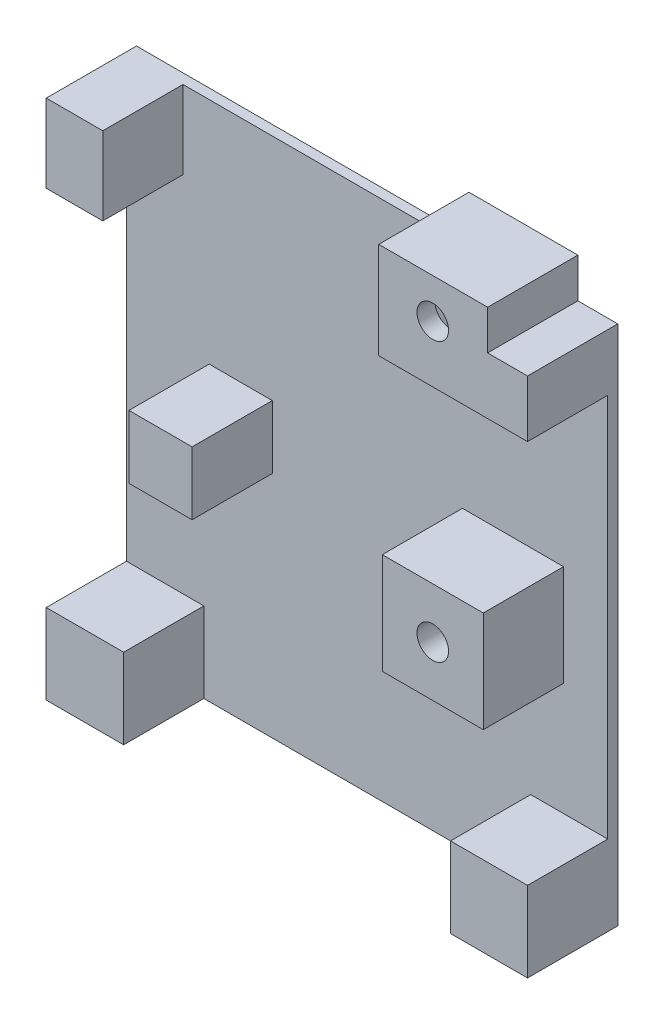
SolidWorks part; units mm, degrees
ref_plane "Front Plane" through (0, 0, 0) normal (0, 0, 1) x (1, 0, 0)
ref_plane "Top Plane" through (0, 0, 0) normal (0, 1, 0) x (1, 0, 0)
ref_plane "Right Plane" through (0, 0, 0) normal (1, 0, 0) x (0, 0, -1)
sketch "Sketch1" plane through (0, 0, 0) normal (0, 0, 1) x (1, 0, 0)
  line L1 (-38.1, -38.1) -> (38.1, -38.1)
  line L2 (-38.1, -38.1) -> (-38.1, 38.1)
  line L3 (-38.1, 38.1) -> (38.1, 38.1)
  line L4 (38.1, -38.1) -> (38.1, 38.1)
  line L5 (-38.1, -38.1) -> (38.1, 38.1) construction
  line L6 (-38.1, 38.1) -> (38.1, -38.1) construction
  point P0 (0, 0)
  dimension "D1" = 76.2
  dimension "D2" = 76.2
extrude "Boss-Extrude1" add sketch "Sketch1" along normal blind 1.5875
sketch "Sketch3" plane through (0, 0, 1.5875) normal (0, 0, 1) x (1, 0, 0)
  line L0 (0, 38.1) -> (0, 0)
  line L1 (-38.1, 38.1) -> (-31.75, 38.1)
  line L2 (-38.1, 38.1) -> (-38.1, 34.925)
  line L3 (-38.1, 34.925) -> (-31.75, 34.925)
  line L4 (-31.75, 38.1) -> (-31.75, 34.925)
  line L5 (38.1, 38.1) -> (-38.1, 38.1) construction
  line L6 (31.75, 38.1) -> (31.75, 34.925)
  line L7 (38.1, 34.925) -> (31.75, 34.925)
  line L8 (38.1, 38.1) -> (38.1, 34.925)
  line L9 (38.1, 38.1) -> (31.75, 38.1)
  line L10 (34.925, -38.1) -> (34.925, -31.75)
  line L11 (-38.1, -38.1) -> (-34.925, -38.1)
  line L12 (-38.1, -38.1) -> (-38.1, -31.75)
  line L13 (-38.1, -31.75) -> (-34.925, -31.75)
  line L14 (-34.925, -38.1) -> (-34.925, -31.75)
  line L15 (38.1, -31.75) -> (34.925, -31.75)
  line L16 (38.1, -38.1) -> (38.1, -31.75)
  line L17 (38.1, -38.1) -> (34.925, -38.1)
  line M6 (38.1, -38.1) -> (38.1, 38.1)
  line M7 (38.1, 38.1) -> (-38.1, 38.1)
  line M8 (-38.1, 38.1) -> (-38.1, -38.1)
  dimension "D1" = 6.35
  dimension "D2" = 3.175
  dimension "D3" = 6.35
  dimension "D4" = 3.175
extrude "Boss-Extrude2" add sketch "Sketch3" along normal blind 12.7 contours L4 L3 M7 M8 | L7 L6 M6 M7 | L12 L13 L14 L11 | L10 L15 L16 L17
sketch "Sketch4" plane through (0, 38.1, 0) normal (0, 1, 0) x (1, 0, 0)
  line L0 (-31.75, -14.2875) -> (-31.75, -1.5875) construction
  line L1 (-38.1, -14.2875) -> (-31.75, -14.2875)
  line L2 (-38.1, -14.2875) -> (-38.1, 0)
  line L3 (-38.1, 0) -> (-31.75, 0)
  line L4 (-31.75, -14.2875) -> (-31.75, 0)
  line L5 (38.1, -14.2875) -> (38.1, 0) construction
  line L6 (31.75, -14.2875) -> (38.1, -14.2875)
  line L7 (31.75, -14.2875) -> (31.75, 0)
  line L8 (31.75, 0) -> (38.1, 0)
  line L9 (38.1, -14.2875) -> (38.1, 0)
  line L10 (38.1, 0) -> (-38.1, 0) construction
  line L11 (-38.1, -14.2875) -> (-38.1, 0) construction
extrude "Boss-Extrude3" add sketch "Sketch4" along normal blind 7.62
sketch "Sketch5" plane through (38.1, 0, 0) normal (1, 0, 0) x (0, 0, -1)
  line L0 (-14.2875, -38.1) -> (0, -38.1) construction
  line L1 (-14.2875, -31.75) -> (0, -31.75)
  line L2 (-14.2875, -31.75) -> (-14.2875, -38.1)
  line L3 (-14.2875, -38.1) -> (0, -38.1)
  line L4 (0, -31.75) -> (0, -38.1)
  line L5 (0, -38.1) -> (0, 45.72) construction
extrude "Boss-Extrude4" add sketch "Sketch5" along normal blind 7.62
sketch "Sketch6" plane through (-38.1, 0, 0) normal (-1, 0, 0) x (0, 0, 1)
  line L0 (14.2875, -38.1) -> (0, -38.1) construction
  line L1 (14.2875, -31.75) -> (0, -31.75)
  line L2 (14.2875, -31.75) -> (14.2875, -38.1)
  line L3 (14.2875, -38.1) -> (0, -38.1)
  line L4 (0, -31.75) -> (0, -38.1)
extrude "Boss-Extrude5" add sketch "Sketch6" along normal blind 7.62
sketch "Sketch7" plane through (0, 0, 0) normal (0, 0, -1) x (-1, 0, 0)
  line L0 (0, 38.1) -> (0, 35.9169)
  line L1 (-31.75, 38.1) -> (31.75, 38.1) construction
  circle A0 centre (-34.925, 41.3917) radius 1.9844
  circle A1 centre (34.925, 41.3917) radius 1.9844
  circle A2 centre (-41.275, -34.925) radius 1.9844
  circle A3 centre (41.275, -34.925) radius 1.9844
  dimension "D1" = 3.9688
  dimension "D2" = 3.9688
extrude "Cut-Extrude2" cut sketch "Sketch7" against normal through all contours A0 | A1 | A2 | A3
sketch "Sketch8" plane through (-38.1, 0, 0) normal (-1, 0, 0) x (0, 0, 1)
  line L0 (14.2875, 34.925) -> (1.5875, 25.7327)
  line L1 (1.5875, 34.925) -> (1.5875, -31.75) construction
  line L2 (1.5875, 25.7327) -> (1.5875, 34.925)
  line L3 (1.5875, 34.925) -> (1.5875, 25.7327)
  line L4 (1.5875, 34.925) -> (14.2875, 34.925)
  line M3 (1.5875, -31.75) -> (1.5875, 34.925)
  line M4 (1.5875, 34.925) -> (14.2875, 34.925)
extrude "Boss-Extrude6" add sketch "Sketch8" against normal blind 76.2 contours L0 M4 M3
sketch "Sketch9" plane through (0, 34.925, 0) normal (0, 1, 0) x (1, 0, 0)
  line L1 (-31.75, -1.5875) -> (31.75, -1.5875)
  line L2 (-31.75, -1.5875) -> (-31.75, -14.2875)
  line L3 (-31.75, -14.2875) -> (31.75, -14.2875)
  line L4 (31.75, -1.5875) -> (31.75, -14.2875)
extrude "Cut-Extrude3" cut sketch "Sketch9" against normal up to next
sketch "Sketch10" plane through (0, -38.1, 0) normal (0, -1, 0) x (1, 0, 0)
  line L0 (-34.925, 14.2875) -> (-26.2574, 1.5875)
  line L1 (-38.1, 14.2875) -> (-31.75, 14.2875) construction
  line L2 (-34.925, 1.5875) -> (34.925, 1.5875) construction
  line L3 (-26.2574, 1.5875) -> (-34.925, 1.5875)
  line L4 (-31.75, 1.5875) -> (-38.1, 1.5875) construction
  line L5 (-34.925, 1.5875) -> (-34.925, 14.2875)
  line L6 (0, 0) -> (0, 7.1603)
  line L7 (34.925, 1.5875) -> (34.925, 14.2875)
  line L8 (26.2574, 1.5875) -> (34.925, 1.5875)
  line L9 (34.925, 14.2875) -> (26.2574, 1.5875)
  line M7 (34.925, 14.2875) -> (34.925, 1.5875)
  line M8 (34.925, 1.5875) -> (-34.925, 1.5875)
  line M9 (-34.925, 1.5875) -> (-34.925, 14.2875)
extrude "Boss-Extrude7" add sketch "Sketch10" against normal blind 6.35 contours L0 M9 M8 | L9 M7 M8
sketch "Sketch11" plane through (0, -38.1, 0) normal (0, -1, 0) x (1, 0, 0)
  line L0 (-45.72, 14.2875) -> (-45.72, 0)
  line L1 (-45.72, 0) -> (45.72, 0)
  line L2 (45.72, 0) -> (45.72, 14.2875)
  line L3 (45.72, 14.2875) -> (34.925, 14.2875)
  line L4 (34.925, 14.2875) -> (26.2574, 1.5875)
  line L5 (26.2574, 1.5875) -> (-26.2574, 1.5875)
  line L6 (-26.2574, 1.5875) -> (-34.925, 14.2875)
  line L7 (-38.1, 14.2875) -> (-31.75, 14.2875) construction
  line L8 (-34.925, 14.2875) -> (-45.72, 14.2875)
extrude "Boss-Extrude8" add sketch "Sketch11" along normal blind 6.35
sketch "Sketch12" plane through (0, 0, 0) normal (0, 0, -1) x (-1, 0, 0)
  line L0 (-38.1, -31.75) -> (-38.1, -44.45)
  line L1 (45.72, -44.45) -> (-45.72, -44.45) construction
  line L3 (-38.1, -31.75) -> (-45.72, -31.75)
  line L4 (-38.1, -31.75) -> (-38.1, -44.45)
  line L5 (-38.1, -44.45) -> (-45.72, -44.45)
  line L6 (-45.72, -31.75) -> (-45.72, -44.45)
  line M9 (-38.1, -31.75) -> (-45.72, -31.75)
  line M10 (-45.72, -31.75) -> (-45.72, -44.45)
  line M11 (-45.72, -44.45) -> (45.72, -44.45)
  circle M20 centre (-41.275, -34.925) radius 1.9844
extrude "Cut-Extrude4" cut sketch "Sketch12" against normal blind 30.48 contours L0 M9 M10 M11 M20
sketch "Sketch13" plane through (0, 0, 0) normal (0, 0, -1) x (-1, 0, 0)
  line L0 (-38.1, 38.1) -> (-23.1, 38.1)
  line L1 (-38.1, -44.45) -> (-38.1, 45.72) construction
  line L2 (-31.75, 38.1) -> (31.75, 38.1) construction
  line L4 (-31.75, 38.1) -> (-38.1, 38.1)
  line L5 (-31.75, 38.1) -> (-31.75, 45.72)
  line L6 (-31.75, 45.72) -> (-38.1, 45.72)
  line L7 (-38.1, 38.1) -> (-38.1, 45.72)
extrude "Cut-Extrude5" cut sketch "Sketch13" against normal blind 30.48 contours L5 L4 L7 L6
sketch "Sketch14" plane through (0, 0, 0) normal (0, 0, -1) x (-1, 0, 0)
  line L0 (-38.1, 38.1) -> (-18.1, 38.1)
  line L2 (-38.1, 38.1) -> (31.75, 38.1) construction
sketch "Sketch15" plane through (0, 38.1, 0) normal (0, 1, 0) x (1, 0, 0)
  line L5 (31.75, -1.5875) -> (38.1, -1.5875)
  line L6 (31.75, -1.5875) -> (31.75, -14.2875)
  line L7 (31.75, -14.2875) -> (38.1, -14.2875)
  line L8 (38.1, -1.5875) -> (38.1, -14.2875)
extrude "Cut-Extrude6" cut sketch "Sketch15" against normal blind 30.48
sketch "Sketch16" plane through (0, 0, 0) normal (0, 0, -1) x (-1, 0, 0)
  line L0 (-38.1, 38.1) -> (-38.1, 43.1)
  line L1 (-38.1, 43.1) -> (-18.1, 43.1)
  line L2 (-18.1, 43.1) -> (-18.1, 29.1)
  line L3 (-18.1, 29.1) -> (-38.1, 29.1)
  line L4 (-38.1, -44.45) -> (-38.1, 38.1) construction
  line L5 (-38.1, 29.1) -> (-38.1, 38.1)
  line L6 (-18.1, 36.1) -> (-23.1, 36.1)
  circle A0 centre (-23.1, 36.1) radius 2.5
extrude "Boss-Extrude9" add sketch "Sketch16" against normal blind 14.2875 contours L5 L0 L1 L2 L3
sketch "Sketch17" plane through (0, 0, 0) normal (0, 0, -1) x (-1, 0, 0)
  line L0 (-18.1, 38.1) -> (-23.1, 38.1)
  line L1 (-38.1, 38.1) -> (-18.1, 38.1) construction
  circle A0 centre (-23.1, 38.1) radius 2.5
extrude "Cut-Extrude7" cut sketch "Sketch17" against normal blind 24.9555
sketch "Sketch18" plane through (0, 0, 0) normal (0, 0, -1) x (-1, 0, 0)
  line L0 (-20.6, 38.1) -> (-25.6, 38.1)
  line L1 (-38.1, 38.1) -> (-18.1, 38.1) construction
  line L9 (-18.4812, 38.1) -> (-20.7906, 42.1)
  line L10 (-20.7906, 42.1) -> (-25.4094, 42.1)
  line L11 (-25.4094, 42.1) -> (-27.7188, 38.1)
  line L12 (-27.7188, 38.1) -> (-25.4094, 34.1)
  line L13 (-25.4094, 34.1) -> (-20.7906, 34.1)
  line L14 (-20.7906, 34.1) -> (-18.4812, 38.1)
  circle A0 centre (-23.1, 38.1) radius 2.5 construction
  circle A1 centre (-23.1, 38.1) radius 4 construction
  circle M7 centre (-23.1, 38.1) radius 2.5
extrude "Cut-Extrude8" cut sketch "Sketch18" against normal blind 11.43 contours L13 L14 L9 L10 L11 L12 M7
sketch "Sketch19" plane through (18.1, 0, 0) normal (-1, 0, 0) x (0, 0, 1)
  line L0 (1.5875, 29.1) -> (14.2875, 29.1)
  line L1 (14.2875, 43.1) -> (14.2875, 29.1) construction
  line L2 (14.2875, 29.1) -> (14.2875, 43.1)
  line L3 (14.2875, 43.1) -> (0, 43.1)
  line L4 (0, 43.1) -> (0, 38.1)
  line L5 (0, 38.1) -> (1.5875, 38.1)
  line L6 (1.5875, 38.1) -> (1.5875, 29.1)
extrude "Boss-Extrude10" add sketch "Sketch19" along normal blind 3.556
sketch "Sketch20" plane through (0, 0, 0) normal (0, 0, -1) x (-1, 0, 0)
  line L0 (-27.7188, 38.1) -> (-18.4812, 38.1)
  line L1 (-23.1, 38.1) -> (-23.1, -5.9)
  line L3 (-31.1, -13.9) -> (-15.1, -13.9)
  line L4 (-31.1, -13.9) -> (-31.1, 2.1)
  line L5 (-31.1, 2.1) -> (-15.1, 2.1)
  line L6 (-15.1, -13.9) -> (-15.1, 2.1)
  line L7 (-31.1, -13.9) -> (-15.1, 2.1) construction
  line L8 (-31.1, 2.1) -> (-15.1, -13.9) construction
  circle A0 centre (-23.1, -5.9) radius 2.5
extrude "Boss-Extrude11" add sketch "Sketch20" against normal blind 14.2875
sketch "Sketch21" plane through (0, 0, 0) normal (0, 0, -1) x (-1, 0, 0)
  line L0 (-27.7188, 38.1) -> (-18.4812, 38.1)
  line L1 (-23.1, 38.1) -> (-23.1, -5.9)
  circle A0 centre (-23.1, -5.9) radius 2.5
extrude "Cut-Extrude9" cut sketch "Sketch21" against normal blind 31.0515
sketch "Sketch22" plane through (0, 0, 0) normal (0, 0, -1) x (-1, 0, 0)
  line L0 (-25.6, -5.9) -> (-20.6, -5.9)
  line L2 (-18.4812, -5.9) -> (-20.7906, -1.9)
  line L3 (-20.7906, -1.9) -> (-25.4094, -1.9)
  line L4 (-25.4094, -1.9) -> (-27.7188, -5.9)
  line L5 (-27.7188, -5.9) -> (-25.4094, -9.9)
  line L6 (-25.4094, -9.9) -> (-20.7906, -9.9)
  line L7 (-20.7906, -9.9) -> (-18.4812, -5.9)
  circle A0 centre (-23.1, -5.9) radius 2.5 construction
  circle A1 centre (-23.1, -5.9) radius 4 construction
  circle M7 centre (-23.1, -5.9) radius 2.5
extrude "Cut-Extrude10" cut sketch "Sketch22" against normal blind 10.16 contours L6 L7 L2 L3 L4 L5 M7
sketch "Sketch23" plane through (0, 43.1, 0) normal (0, 1, 0) x (1, 0, 0)
  line L1 (38.1, 0) -> (14.544, 0)
  line L2 (38.1, 0) -> (38.1, -14.2875)
  line L3 (38.1, -14.2875) -> (14.544, -14.2875)
  line L4 (14.544, 0) -> (14.544, -14.2875)
extrude "Boss-Extrude12" add sketch "Sketch23" along normal blind 1.27
sketch "Sketch24" plane through (0, 0, 0) normal (0, 0, -1) x (-1, 0, 0)
  line L2 (31.75, 38.1) -> (38.1, 38.1)
  line L3 (31.75, 38.1) -> (31.75, 45.72)
  line L4 (31.75, 45.72) -> (38.1, 45.72)
  line L5 (38.1, 38.1) -> (38.1, 45.72)
extrude "Cut-Extrude11" cut sketch "Sketch24" against normal blind 30.988
sketch "Sketch25" plane through (0, 0, 0) normal (0, 0, -1) x (-1, 0, 0)
  line L1 (38.1, -31.75) -> (45.72, -31.75)
  line L2 (38.1, -31.75) -> (38.1, -44.45)
  line L3 (38.1, -44.45) -> (45.72, -44.45)
  line L4 (45.72, -31.75) -> (45.72, -44.45)
extrude "Cut-Extrude12" cut sketch "Sketch25" against normal blind 30.988
sketch "Sketch26" plane through (38.1, 0, 0) normal (1, 0, 0) x (0, 0, -1)
  line L0 (-1.5875, -31.75) -> (-1.5875, -44.45)
  line L2 (-1.5875, -31.75) -> (-14.2875, -31.75)
  line L3 (-1.5875, -31.75) -> (-1.5875, -44.45)
  line L4 (-1.5875, -44.45) -> (-14.2875, -44.45)
  line L5 (-14.2875, -31.75) -> (-14.2875, -44.45)
  line M3 (-1.5875, -31.75) -> (-14.2875, -31.75)
  line M4 (-14.2875, -31.75) -> (-14.2875, -44.45)
  line M5 (-14.2875, -44.45) -> (0, -44.45)
extrude "Boss-Extrude13" add sketch "Sketch26" against normal blind 12.192 contours L0 M3 M4 M5
sketch "Sketch27" plane through (0, 0, 0) normal (0, 0, -1) x (-1, 0, 0)
  line L0 (-38.1, -44.45) -> (38.1, 38.1)
  line L1 (5, -8.175) -> (10.0039, -8.175)
  line L2 (-5, 1.825) -> (5, 1.825)
  line L3 (-5, 1.825) -> (-5, -8.175)
  line L4 (-5, -8.175) -> (5, -8.175)
  line L5 (5, 1.825) -> (5, -8.175)
  line L6 (-5, 1.825) -> (5, -8.175) construction
  line L7 (-5, -8.175) -> (5, 1.825) construction
  line L8 (10.0039, -8.175) -> (10.0039, 1.825)
  line L9 (10.0039, 1.825) -> (5, 1.825)
  line L10 (25.0079, -8.175) -> (15.0079, -8.175)
  line L11 (15.0079, 1.825) -> (15.0079, -8.175)
  line L12 (25.0079, 1.825) -> (15.0079, 1.825)
  line L13 (25.0079, 1.825) -> (25.0079, -8.175)
  point P4 (0, -3.175)
sketch "Sketch28" plane through (-38.1, 0, 0) normal (-1, 0, 0) x (0, 0, 1)
  line L1 (1.5875, -31.75) -> (14.2875, -31.75)
  line L2 (1.5875, -31.75) -> (1.5875, -44.45)
  line L3 (1.5875, -44.45) -> (14.2875, -44.45)
  line L4 (14.2875, -31.75) -> (14.2875, -44.45)
extrude "Boss-Extrude15" add sketch "Sketch28" against normal blind 12.2555
sketch "Sketch29" plane through (-38.1, 0, 0) normal (-1, 0, 0) x (0, 0, 1)
  line L1 (1.5875, 38.1) -> (14.2875, 38.1)
  line L2 (1.5875, 38.1) -> (1.5875, 25.7327)
  line L3 (1.5875, 25.7327) -> (14.2875, 25.7327)
  line L4 (14.2875, 38.1) -> (14.2875, 25.7327)
extrude "Boss-Extrude16" add sketch "Sketch29" against normal blind 8.9535
sketch "Sketch30" plane through (0, 0, 0) normal (0, 0, -1) x (-1, 0, 0)
  line L0 (-27.7188, 38.1) -> (-31.7828, 38.1)
  line L2 (-31.7828, 38.1) -> (-38.1, 38.1)
  line L3 (-31.7828, 38.1) -> (-31.7828, 44.37)
  line L4 (-31.7828, 44.37) -> (-38.1, 44.37)
  line L5 (-38.1, 38.1) -> (-38.1, 44.37)
  line M6 (-14.544, 44.37) -> (-38.1, 44.37)
  line M7 (-38.1, 44.37) -> (-38.1, -44.45)
extrude "Cut-Extrude13" cut sketch "Sketch30" against normal blind 32.8295 contours L2 L3 M6 M7
sketch "Sketch33" plane through (0, 38.1, 0) normal (0, 1, 0) x (1, 0, 0)
  line L0 (38.1, 0) -> (38.1, -1.524)
  line L1 (38.1, -14.2875) -> (38.1, 0) construction
  line L3 (38.1, -1.524) -> (31.7828, -1.524)
  line L4 (38.1, -1.524) -> (38.1, -14.2875)
  line L5 (38.1, -14.2875) -> (31.7828, -14.2875)
  line L6 (31.7828, -1.524) -> (31.7828, -14.2875)
extrude "Boss-Extrude17" add sketch "Sketch27" against normal blind 14.2875 contours L13 L12 L11 L10
